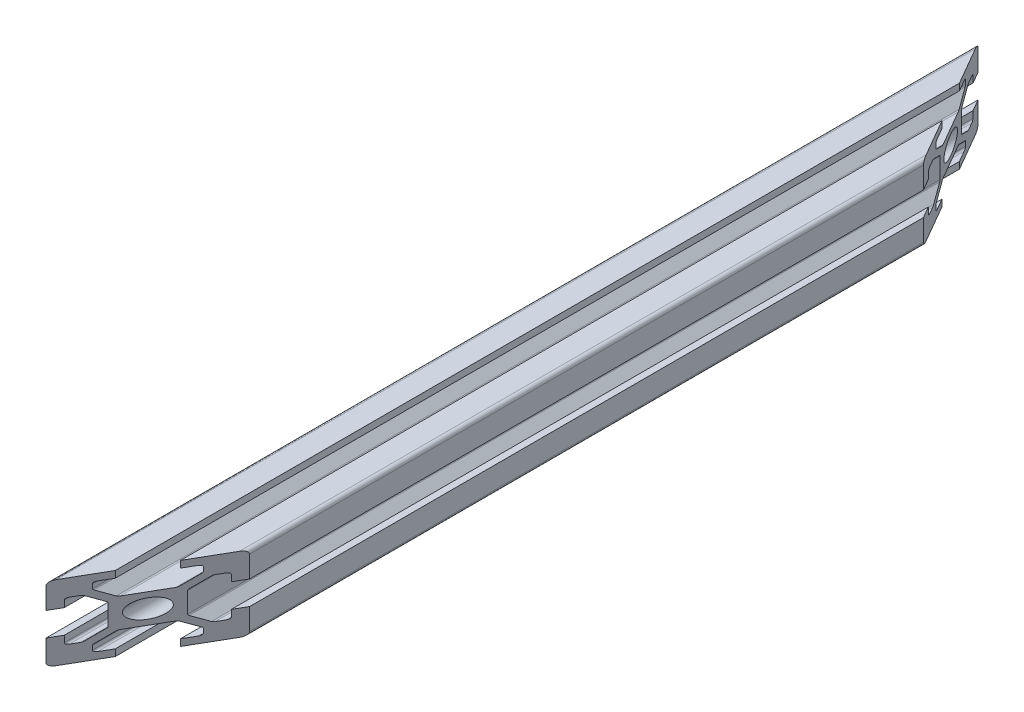
SolidWorks part; units mm, degrees
material "1060 Alloy"
ref_plane "Front Plane" through (0, 0, 0) normal (0, 0, 1) x (1, 0, 0)
ref_plane "Top Plane" through (0, 0, 0) normal (0, 1, 0) x (1, 0, 0)
ref_plane "Right Plane" through (0, 0, 0) normal (1, 0, 0) x (0, 0, -1)
sketch "Sketch1" plane through (0, 0, 0) normal (0, 0, 1) x (1, 0, 0)
  line L0 (20, 0) -> (-8.059, 28.059) construction
  line L1 (0, 0) -> (6.8, 0)
  line L2 (0, 0) -> (0, 6.8)
  line L3 (0, 20) -> (6.8, 20)
  line L4 (20, 0) -> (20, 6.8)
  line L5 (6.8, 20) -> (6.8, 18.2)
  line L6 (20, 20) -> (8.2322, 8.2322) construction
  line L7 (12.95, 6.1) -> (7.05, 6.1)
  line L8 (13.9, 7.05) -> (13.9, 12.95)
  line L9 (12.95, 13.9) -> (7.05, 13.9)
  line L10 (6.1, 7.05) -> (6.1, 12.95)
  line L11 (13.9, 6.1) -> (6.1, 13.9) construction
  line L12 (13.9, 13.9) -> (6.1, 6.1) construction
  line L13 (4.55, 16.4) -> (7.05, 13.9)
  line L14 (13.2, 18.2) -> (13.2, 20)
  line L15 (1.8, 6.8) -> (0, 6.8)
  line L16 (0, 13.2) -> (0, 20)
  line L17 (0, 13.2) -> (1.8, 13.2)
  line L18 (10, 10) -> (10, 13.9) construction
  line L19 (16.4, 4.55) -> (13.9, 7.05)
  line L20 (4.55, 16.4) -> (4.55, 18.2)
  line L21 (4.55, 18.2) -> (6.8, 18.2)
  line L22 (13.2, 18.2) -> (15.45, 18.2)
  line L23 (15.45, 18.2) -> (15.45, 16.4)
  line L24 (15.45, 16.4) -> (12.95, 13.9)
  line L25 (16.4, 4.55) -> (18.2, 4.55)
  line L26 (18.2, 4.55) -> (18.2, 6.8)
  line L27 (20, 6.8) -> (18.2, 6.8)
  line L28 (18.2, 13.2) -> (20, 13.2)
  line L29 (18.2, 13.2) -> (18.2, 15.45)
  line L30 (18.2, 15.45) -> (16.4, 15.45)
  line L31 (16.4, 15.45) -> (13.9, 12.95)
  line L32 (1.8, 4.55) -> (3.6, 4.55)
  line L33 (3.6, 15.45) -> (6.1, 12.95)
  line L34 (3.6, 15.45) -> (1.8, 15.45)
  line L35 (1.8, 15.45) -> (1.8, 13.2)
  line L36 (0, 13.2) -> (1.8, 13.2)
  line L37 (1.8, 6.8) -> (0, 6.8)
  line L38 (3.6, 4.55) -> (6.1, 7.05)
  line L39 (1.8, 6.8) -> (1.8, 4.55)
  line L40 (15.45, 3.6) -> (12.95, 6.1)
  line L41 (4.55, 3.6) -> (7.05, 6.1)
  line L42 (4.55, 1.8) -> (4.55, 3.6)
  line L43 (6.8, 1.8) -> (4.55, 1.8)
  line L44 (6.8, 1.8) -> (6.8, 0)
  line L45 (15.45, 3.6) -> (15.45, 1.8)
  line L46 (15.45, 1.8) -> (13.2, 1.8)
  line L47 (13.2, 0) -> (13.2, 1.8)
  line L48 (13.2, 20) -> (20, 20)
  line L49 (20, 13.2) -> (20, 20)
  line L50 (13.2, 0) -> (20, 0)
  line L51 (6.1, 6.1) -> (-5.5045, -5.5045) construction
  circle A0 centre (10, 10) radius 2.5
  point P25 (10, 16.4)
  point P39 (13.2, 19.1)
  point P46 (0.9, 6.8)
  dimension "D3" = 5
  dimension "D2" = 20
  dimension "D4" = 7.8
  dimension "D5" = 7.8
  dimension "D6" = 6.8
  dimension "D7" = 6.8
  dimension "D8" = 1.8
  dimension "D9" = 10.9
  dimension "D10" = 1.8
  dimension "D11" = 10.9
  dimension "D12" = 20
extrude "Boss-Extrude1" add sketch "Sketch1" along normal blind 250 contours L47 L50 L4 L27 L26 L25 L19 L8 L31 L30 L29 L28 L49 L48 L14 L22 L23 L24 L9 L13 L20 L21 L5 L3 L16 L17 L35 L34 L33 L10 L38 L32 L39 L15 L2 L1 L44 L43 L42 L41 L7 L40 L45 L46 A0
fillet "Fillet1" radius 1 4 edges at (20, 20, 125) (20, 0, 125) (0, 0, 125) (0, 20, 125)
fillet "Fillet2" radius 0.5 6 edges at (4.55, 18.2, 125) (4.55, 16.4, 125) (7.05, 13.9, 125) (15.45, 18.2, 125) (15.45, 16.4, 125) (12.95, 13.9, 125)
fillet "Fillet3" radius 0.5 6 edges at (18.2, 15.45, 125) (16.4, 15.45, 125) (13.9, 12.95, 125) (18.2, 4.55, 125) (13.9, 7.05, 125) (16.4, 4.55, 125)
fillet "Fillet4" radius 0.5 6 edges at (1.8, 15.45, 125) (3.6, 15.45, 125) (6.1, 12.95, 125) (3.6, 4.55, 125) (1.8, 4.55, 125) (6.1, 7.05, 125)
fillet "Fillet5" radius 0.5 6 edges at (7.05, 6.1, 125) (4.55, 3.6, 125) (4.55, 1.8, 125) (15.45, 1.8, 125) (15.45, 3.6, 125) (12.95, 6.1, 125)
sketch "Sketch4" plane through (0, 0, 0) normal (0, -1, 0) x (1, 0, 0)
  line L0 (20, 250) -> (20, 215.359)
  line L1 (20, 250) -> (20, 0) construction
  line L2 (20, 215.359) -> (0, 250)
  line L3 (0, 250) -> (20, 250)
  dimension "D1" = 30
extrude "Cut-Extrude3" cut sketch "Sketch4" against normal through all contours L2 L3 L0
sketch "Sketch6" plane through (0, 0, 0) normal (0, -1, 0) x (1, 0, 0)
  line L0 (20, 0) -> (0, 0)
  line L1 (0, 0) -> (20, 34.641)
  line L2 (20, 215.359) -> (20, 0) construction
  line L3 (20, 34.641) -> (20, 0)
  dimension "D1" = 30
extrude "Cut-Extrude5" cut sketch "Sketch6" against normal through all
